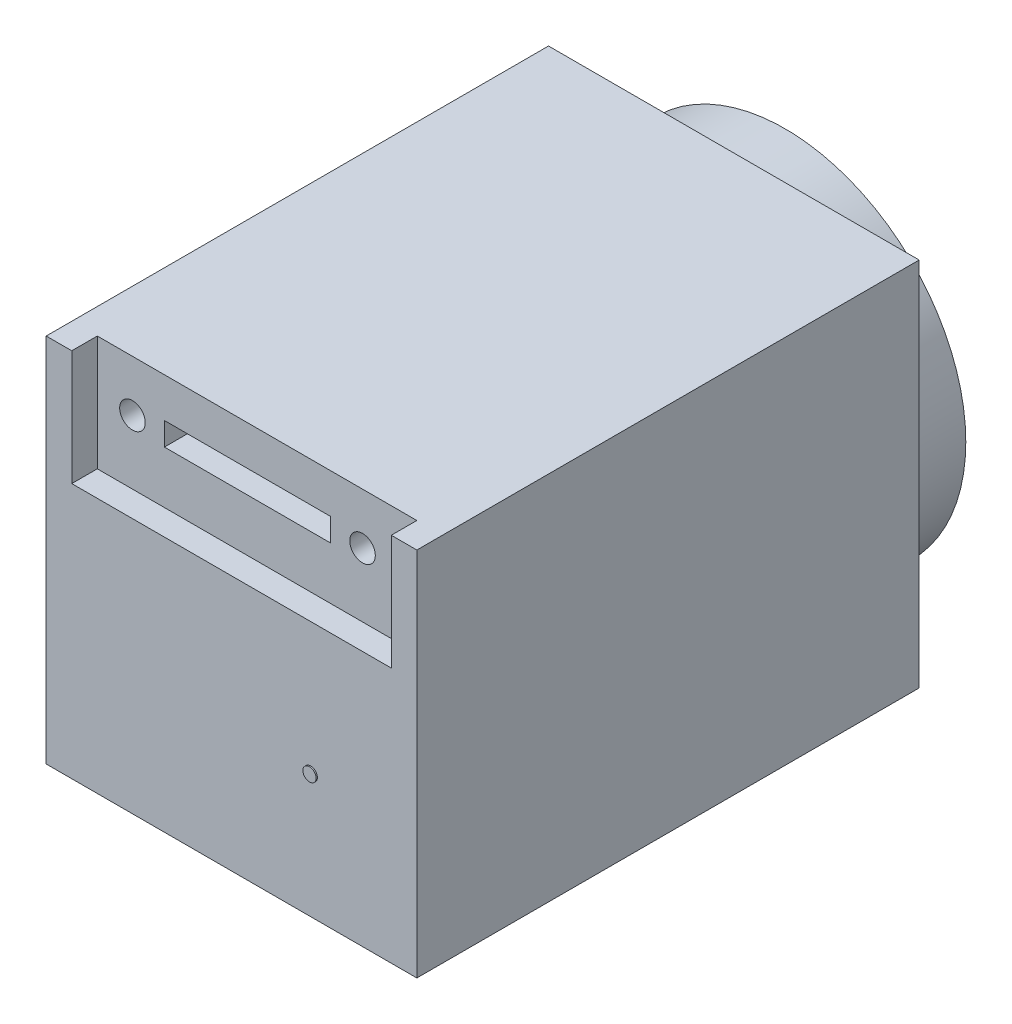
SolidWorks part; units mm, degrees
ref_plane "Front Plane" through (0, 0, 0) normal (0, 0, 1) x (1, 0, 0)
ref_plane "Top Plane" through (0, 0, 0) normal (0, 1, 0) x (1, 0, 0)
ref_plane "Right Plane" through (0, 0, 0) normal (1, 0, 0) x (0, 0, -1)
sketch "Sketch2" plane through (0, 0, 0) normal (0, 0, 1) x (1, 0, 0)
  line L1 (-38.1246, 18.1589) -> (-9.1246, 18.1589)
  line L2 (-38.1246, 18.1589) -> (-38.1246, -10.8411)
  line L3 (-38.1246, -10.8411) -> (-9.1246, -10.8411)
  line L4 (-9.1246, 18.1589) -> (-9.1246, -10.8411)
  dimension "D1" = 29
  dimension "D2" = 29
extrude "Boss-Extrude1" add sketch "Sketch2" along normal blind 39.3
sketch "Sketch3" plane through (0, 0, 0) normal (0, 0, -1) x (-1, 0, 0)
  line L0 (9.1246, 18.1589) -> (38.1246, -10.8411) construction
  circle A0 centre (23.6246, 3.6589) radius 14.15
  circle A1 centre (23.6246, 3.6589) radius 12.7
  point P7 (23.6246, 3.6589)
  dimension "D1" = 25.4
  dimension "D2" = 28.3
extrude "Boss-Extrude2" add sketch "Sketch3" along normal blind 4
sketch "Sketch4" plane through (0, 0, 39.3) normal (0, 0, 1) x (1, 0, 0)
  line L0 (-9.1246, 18.1589) -> (-38.1246, 18.1589) construction
  line L1 (-11.1246, 18.1589) -> (-36.1246, 18.1589)
  line L2 (-11.1246, 18.1589) -> (-11.1246, 9.1589)
  line L3 (-11.1246, 9.1589) -> (-36.1246, 9.1589)
  line L4 (-36.1246, 18.1589) -> (-36.1246, 9.1589)
  line L5 (-38.1246, 18.1589) -> (-9.1246, 18.1589) construction
  line L6 (-38.1246, -10.8411) -> (-9.1246, -10.8411) construction
  line L7 (-38.1246, 18.1589) -> (-38.1246, -10.8411) construction
  point P8 (-23.6246, 18.1589)
  point P9 (-23.6246, 18.1589)
  dimension "D1" = 20
  dimension "D2" = 2
extrude "Cut-Extrude1" cut sketch "Sketch4" against normal blind 2
sketch "Sketch5" plane through (0, 0, 37.3) normal (0, 0, 1) x (1, 0, 0)
  line L0 (-38.1246, -10.8411) -> (-9.1246, -10.8411) construction
  line L1 (-38.1246, 18.1589) -> (-38.1246, -10.8411) construction
  line L2 (-33.3746, 14.1589) -> (-15.3746, 14.1589) construction
  line L3 (-30.8746, 15.0589) -> (-17.8746, 15.0589)
  line L4 (-30.8746, 15.0589) -> (-30.8746, 13.2589)
  line L5 (-30.8746, 13.2589) -> (-17.8746, 13.2589)
  line L6 (-17.8746, 15.0589) -> (-17.8746, 13.2589)
  circle A0 centre (-33.3746, 14.1589) radius 1
  circle A1 centre (-15.3746, 14.1589) radius 1
  point P14 (-30.8746, 14.1589)
  point P15 (-24.3746, 15.0589)
  point P16 (-24.3746, 14.1589)
  dimension "D3" = 2
  dimension "D4" = 2
  dimension "D1" = 25
  dimension "D2" = 4.75
  dimension "D5" = 18
  dimension "D6" = 1.8
  dimension "D7" = 13
extrude "Cut-Extrude2" cut sketch "Sketch5" against normal blind 5
sketch "Sketch6" plane through (0, 0, 39.3) normal (0, 0, 1) x (1, 0, 0)
  line L0 (-38.1246, 18.1589) -> (-38.1246, -10.8411) construction
  line L1 (-38.1246, -10.8411) -> (-9.1246, -10.8411) construction
  circle A0 centre (-17.4246, -1.1411) radius 0.5175
  dimension "D1" = 20.7
  dimension "D2" = 9.7
extrude "Boss-Extrude3" add sketch "Sketch6" along normal blind 0.1
sketch "Sketch7" plane through (0, -10.8411, 0) normal (0, -1, 0) x (1, 0, 0)
  line L0 (-38.1246, 39.3) -> (-9.1246, 0) construction
  circle A0 centre (-23.4173, 19.369) radius 3
  dimension "D1" = 6
extrude "Cut-Extrude3" cut sketch "Sketch7" against normal blind 7
